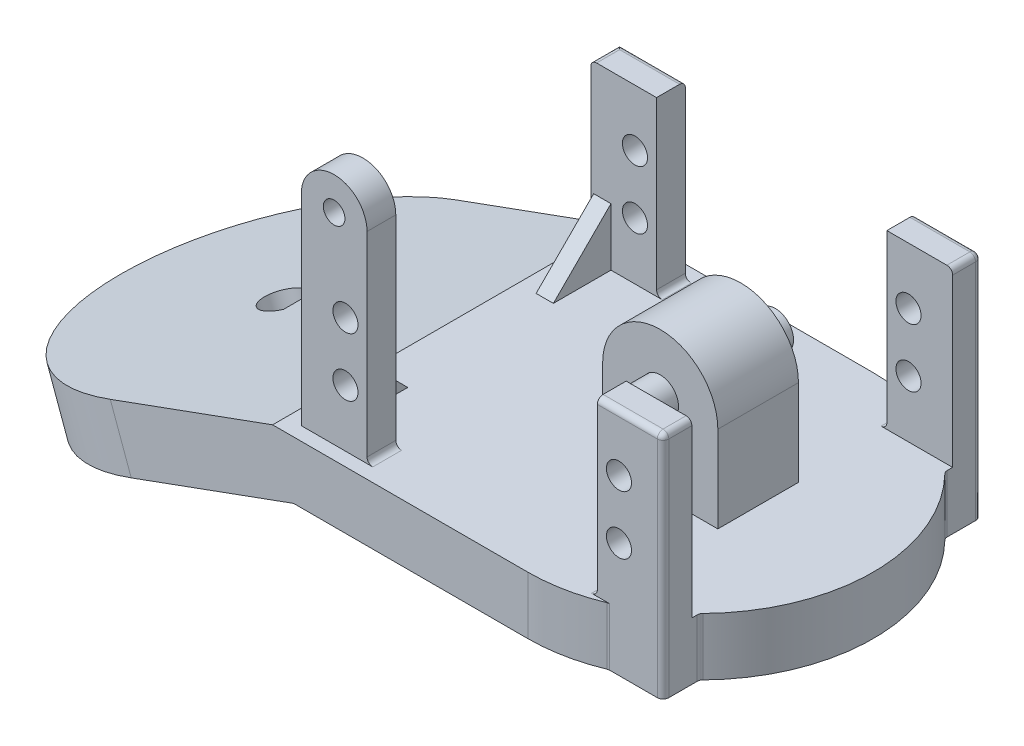
SolidWorks part; units mm, degrees
ref_plane "Plan de face" through (0, 0, 0) normal (0, 0, 1) x (1, 0, 0)
ref_plane "Plan de dessus" through (0, 0, 0) normal (0, 1, 0) x (1, 0, 0)
ref_plane "Plan de droite" through (0, 0, 0) normal (1, 0, 0) x (0, 0, -1)
sketch "Esquisse5" plane through (0, 0, 0) normal (0, 1, 0) x (1, 0, 0)
  line L0 (42.5, 0) -> (-42.5, 0) construction
  line L1 (42.5, -30) -> (-42.5, -30)
  line L2 (42.5, 30) -> (-42.5, 30)
  arc A0 (42.5, -30) -> (42.5, 30) centre (42.5, 0) ccw
  arc A1 (-42.5, 30) -> (-42.5, -30) centre (-42.5, 0) ccw
  point P2 (0, 0)
  dimension "D2" = 30
  dimension "D1" = 85
extrude "Boss.-Extru.3" add sketch "Esquisse5" along normal mid plane 10
sketch "Esquisse36" plane through (0, 0, 0) normal (0, 0, 1) x (1, 0, 0)
  line L0 (0, 0) -> (9.0993, -25)
  line L1 (9.0993, -25) -> (-112.5, -25)
  line L2 (-112.5, -25) -> (-112.5, 35)
  line L3 (-112.5, 35) -> (-12.739, 35)
  line L4 (-12.739, 35) -> (0, 0)
  line L5 (42.5, -5) -> (-42.5, -5) construction
  line L6 (42.5, 5) -> (-42.5, 5) construction
  line L7 (-42.5, 5) -> (-42.5, -5) construction
  dimension "D1" = 180
  dimension "D2" = 20
  dimension "D3" = 70
  dimension "D4" = 30
  dimension "D5" = 70
sketch "Esquisse7" plane through (0, 0, 0) normal (0, 0, 1) x (1, 0, 0)
  line L0 (42.5, 5) -> (32.5, 5)
  line L1 (-42.5, 5) -> (42.5, 5) construction
  line L2 (32.5, 5) -> (32.5, 20)
  line L3 (32.5, 20) -> (52.5, 20)
  line L4 (52.5, 20) -> (52.5, 5)
  line L5 (72.5, 5) -> (42.5, 5) construction
  line L6 (52.5, 5) -> (42.5, 5)
  arc A0 (32.5, 20) -> (52.5, 20) centre (42.5, 20) cw
  circle A1 centre (42.5, 20) radius 3.175
  dimension "D1" = 10
  dimension "D3" = 6.35
  dimension "D2" = 15
extrude "Boss.-Extru.5" add sketch "Esquisse7" along normal mid plane 14 contours A1 L3 A0 | A1 L3 L2 L0 L6 L4
sketch "Esquisse10" plane through (0, -5, 0) normal (0, -1, 0) x (1, 0, 0)
  point P0 (42.5, 0)
ref_plane "Plan1" through (0, 0, 22.64) normal (0, 0, 1) x (1, 0, 0)
sketch "Esquisse13" plane through (0, 0, 22.64) normal (0, 0, 1) x (1, 0, 0)
  line L0 (-42.5, 5) -> (42.5, 5) construction
  line L1 (5.8, 5) -> (58.63, 5)
  line L2 (5.8, 5) -> (5.8, 29.91) construction
  line L3 (5.8, 29.91) -> (58.63, 29.91) construction
  line L4 (58.63, 5) -> (58.63, 29.91) construction
  line L5 (5.8, 5) -> (0.8, 5)
  line L6 (0.8, 5) -> (0.8, 34.91)
  line L7 (0.8, 34.91) -> (63.63, 34.91)
  line L8 (63.63, 34.91) -> (63.63, 5)
  line L9 (63.63, 5) -> (58.63, 5)
  line L10 (63.63, 5) -> (58.63, 5)
  line L11 (0.8, 5) -> (5.8, 5)
  line L12 (12.215, 5) -> (12.215, 29.91)
  line L13 (12.215, 29.91) -> (52.215, 29.91)
  line L14 (52.215, 29.91) -> (52.215, 5)
  line L15 (52.215, 5) -> (12.215, 5)
  circle A0 centre (42.5, 20) radius 3.175 construction
  circle A2 centre (55.97, 25.08) radius 2.18
  circle A3 centre (55.97, 14.92) radius 2.18
  circle A4 centre (8.47, 25.08) radius 2.18
  circle A5 centre (8.47, 14.92) radius 2.18
  point P6 (58.63, 17.455)
  point P24 (32.215, 29.91)
  point P26 (32.215, 34.91)
  dimension "D4" = 5
  dimension "D7" = 4.36
  dimension "D8" = 47.5
  dimension "D12" = 10.16
  dimension "D1" = 52.83
  dimension "D2" = 16.13
  dimension "D3" = 24.91
  dimension "D5" = 4.83
  dimension "D6" = 2.67
  dimension "D9" = 47.5
  dimension "D10" = 0
  dimension "D11" = 0
  dimension "D13" = 0
  dimension "D14" = 5
  dimension "D15" = 5
  dimension "D16" = 40
  dimension "D17" = 0
  dimension "D18" = 0
extrude "Boss.-Extru.8" add sketch "Esquisse13" along normal blind 5 contours L13 L14 L1 L9 L8 L7 L6 L5 L12 A5 A4 A3 A2
sketch "Esquisse47" plane through (0, 0, 27.64) normal (0, 0, 1) x (1, 0, 0)
  line L0 (52.215, 29.91) -> (52.215, 5) construction
  line L1 (12.215, 29.91) -> (52.215, 29.91)
  line L2 (12.215, 29.91) -> (12.215, 34.91)
  line L3 (12.215, 34.91) -> (52.215, 34.91)
  line L4 (52.215, 29.91) -> (52.215, 34.91)
  line L5 (12.215, 29.91) -> (52.215, 34.91) construction
  line L6 (12.215, 34.91) -> (52.215, 29.91) construction
  line L7 (12.215, 5) -> (12.215, 29.91) construction
  line L8 (12.215, 29.91) -> (52.215, 29.91) construction
  line L9 (0.8, 34.91) -> (63.63, 34.91) construction
  point P4 (32.215, 32.41)
extrude "Enlèv. mat.-Extru.8" cut sketch "Esquisse47" against normal up to next
ref_plane "Plan12" through (2.8, 0, 0) normal (-1, 0, 0) x (0, 0, 1)
mirror "Symétrie2" about plane through (0, 0, 0) normal (0, 0, 1) of "Enlèv. mat.-Extru.8", "Boss.-Extru.8"
sketch "Esquisse14" plane through (0, 0, 0) normal (0, 0, 1) x (1, 0, 0)
  point P0 (42.5, 20)
sketch "Esquisse33" plane through (0, 5, 0) normal (0, -1, 0) x (1, 0, 0)
  line L0 (54.1632, -27.64) -> (63.63, -27.64) construction
  line L1 (63.63, 27.64) -> (54.1632, 27.64)
  line L2 (63.63, 27.64) -> (63.63, -27.64)
  line L3 (63.63, -27.64) -> (54.1632, -27.64)
  line L4 (54.1632, 27.64) -> (54.1632, -27.64)
  dimension "D1" = 0
  dimension "D2" = 0
extrude "Boss.-Extru.10" add sketch "Esquisse33" along normal up to surface (10 mm away) up to face at (0, -5, 0)
sketch "Esquisse34" plane through (0, 0, 0) normal (0, 1, 0) x (1, 0, 0)
  line L0 (0, 0) -> (0, 29.4868) construction
extrude "Enlèv. mat.-Extru.6" cut sketch "Esquisse36" against normal mid plane 130
ref_plane "Plan11" through (0, 0, 0) normal (-0.342, 0.9397, 0) x (0, 0, -1)
sketch "Esquisse35" plane through (0, 0, 0) normal (-0.342, 0.9397, 0) x (0, 0, -1)
  circle A0 centre (0, 30) radius 30
  dimension "D1" = 60
  dimension "D2" = 0
extrude "Boss.-Extru.11" add sketch "Esquisse35" along normal mid plane 10.64
sketch "Esquisse37" plane through (0, 0, 0) normal (0, 0, 1) x (1, 0, 0)
sketch "Esquisse38" plane through (-1.8195, 4.9992, 0) normal (-0.342, 0.9397, 0) x (0.9397, 0.342, 0)
  point P1 (-30, 0)
sketch "Esquisse39" plane through (1.8195, -4.9992, 0) normal (0.342, -0.9397, 0) x (0.9397, 0.342, 0)
  point P0 (-30, 0)
sketch "Esquisse40" plane through (0, 0, 0) normal (0, 0, 1) x (1, 0, 0)
  line L0 (-26.3712, -15.2598) -> (-30.0103, -5.2614)
  line L1 (-26.3712, -15.2598) -> (1.8195, -4.9992)
  line L2 (-30.0103, -5.2614) -> (-1.8195, 4.9992)
  line L3 (1.8195, -4.9992) -> (-1.8195, 4.9992)
  dimension "D1" = 0
extrude "Boss.-Extru.12" add sketch "Esquisse40" along normal mid plane 60
sketch "Esquisse41" plane through (-1.8195, 4.9992, 0) normal (-0.342, 0.9397, 0) x (0.9397, 0.342, 0)
  line L0 (-27.46, -2.2602) -> (-27.46, 2.2602)
  line L1 (0, -30) -> (0, 30) construction
  arc A1 (-27.46, -2.2602) -> (-27.46, 2.2602) centre (-30, 0) cw
  point P4 (-33.4, 0)
  dimension "D2" = 3.4
  dimension "D3" = 5.94
extrude "Enlèv. mat.-Extru.7" cut sketch "Esquisse41" against normal blind 60
sketch "Esquisse42" plane through (0, 0, 27.64) normal (0, 0, 1) x (1, 0, 0)
  line L0 (0.8, 34.91) -> (0.8, 39.91)
  line L1 (0.8, 39.91) -> (12.215, 39.91)
  line L2 (12.215, 39.91) -> (12.215, 34.91)
  line L3 (0.8, 34.91) -> (12.215, 34.91) construction
  line L4 (12.215, 34.91) -> (0.8, 34.91)
  line L5 (12.215, 5) -> (12.215, 34.91) construction
  arc A0 (0.8, 39.91) -> (12.215, 39.91) centre (6.5075, 39.91) cw
  circle A1 centre (6.5075, 39.91) radius 1.875
  line M15 (63.63, 34.91) -> (52.215, 34.91)
  dimension "D3" = 3.75
  dimension "D1" = 5
  dimension "D2" = 0
extrude "Boss.-Extru.13" add sketch "Esquisse42" against normal up to surface (5 mm away) contours A1 L1 A0 | A1 L1 L0 L2 M15
sketch "Esquisse45" plane through (2.8, 0, 0) normal (-1, 0, 0) x (0, 0, 1)
  line L0 (22.64, 14.9996) -> (12.64, 4.9996)
  line L1 (22.64, 5) -> (22.64, 39.91) construction
  line L2 (30, 4.9996) -> (-30, 4.9996) construction
  dimension "D1" = 10
  dimension "D2" = 10
rib "Nervure4" sketch "Esquisse45" sketch "Esquisse45" thickness 3 extrusion direction parallel to sketch draft on no parameters "D1"=3
fillet "Congé1" radius 1 6 edges at (54.1632, 0, 27.64) (63.63, 14.955, -27.64) (54.1632, 0, -27.64) (63.63, 14.955, 27.64) (63.63, 0, 21.2961) (63.63, 0, -21.2961)
mirror "Symétrie3" about plane through (0, 0, 0) normal (0, 0, 1) of "Nervure4"
fillet "Congé2" radius 1 12 edges at (63.63, 34.91, 24.64) (63.3371, 34.91, 27.3471) (63.63, 34.91, -24.64) (63.3371, 34.91, -27.3471) (0.8, 34.91, -25.14) (57.4225, 34.91, -27.64) (6.5075, 34.91, -27.64) (52.215, 5, 25.14) (12.215, 5, -25.14) (57.4225, 34.91, 27.64) (12.215, 5, 25.14) (52.215, 5, -25.14)
sketch "Esquisse48" plane through (0, 0, 0) normal (0, 0, 1) x (1, 0, 0)
  circle A0 centre (42.5, 20) radius 3.15
  dimension "D1" = 6.3
extrude "Boss.-Extru.14" add sketch "Esquisse48" along normal blind 13 and the other way blind 13
